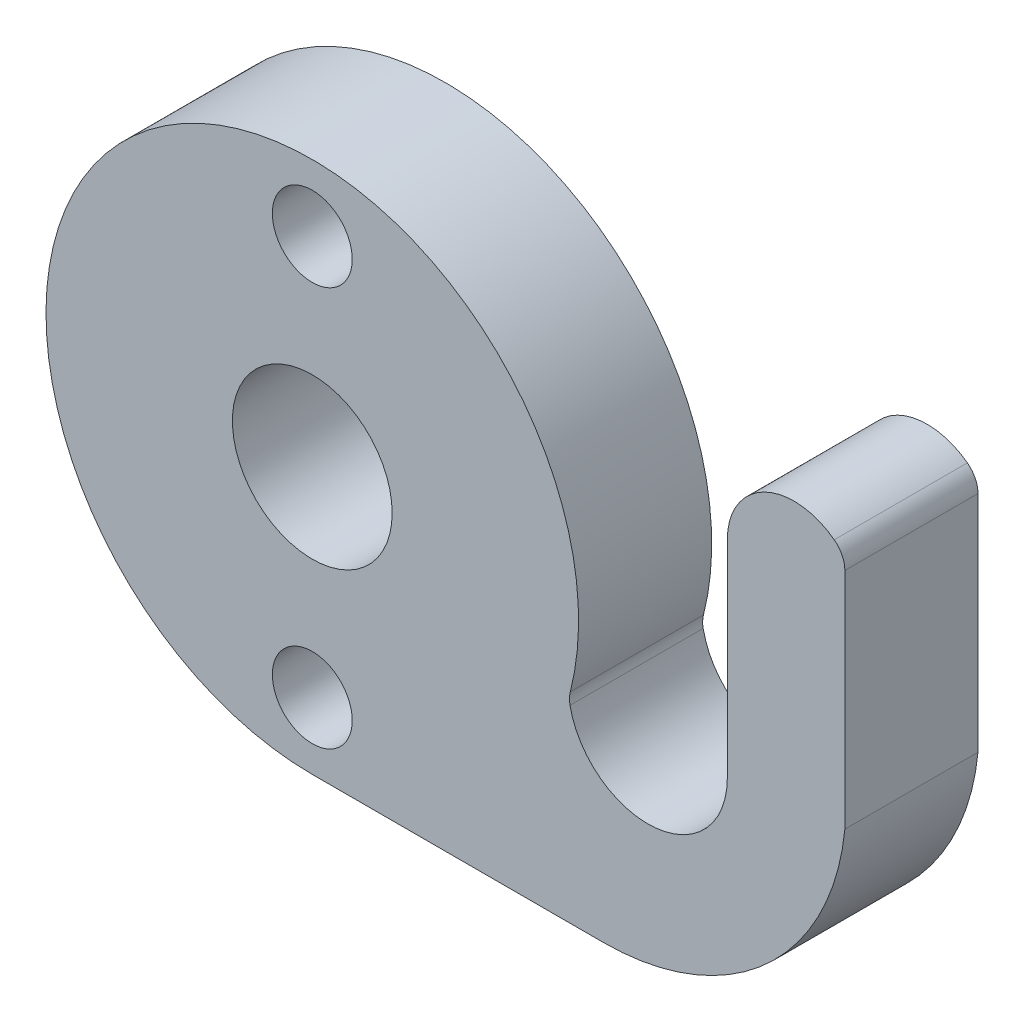
SolidWorks part; units mm, degrees
ref_plane "Front" through (0, 0, 0) normal (0, 0, 1) x (1, 0, 0)
ref_plane "Top" through (0, 0, 0) normal (0, 1, 0) x (1, 0, 0)
ref_plane "Right" through (0, 0, 0) normal (1, 0, 0) x (0, 0, -1)
sketch "Esquisse1" plane through (0, 0, 0) normal (0, 0, 1) x (1, 0, 0)
  line L0 (10.586, -2.3263) -> (10.586, 5.428)
  line L3 (-5, -10) -> (5.9334, -10)
  line L4 (15, 7.0573) -> (15, -1.7796)
  line L5 (-15, 10) -> (0, 0) construction
  line L6 (-15, -10) -> (15, 10) construction
  line L7 (15, 7.0573) -> (15, -1.7796)
  line L8 (-5, -10) -> (5.9334, -10)
  line L9 (7.9353, -5.2902) -> (15, -10) construction
  arc A0 (4.6398, -2.6597) -> (-5, -10) centre (-5, 0) ccw
  arc A1 (4.6398, -2.6597) -> (10.586, -2.3263) centre (7.6035, -2.3263) ccw
  arc A2 (5.9334, -10) -> (15, 0) centre (5.9334, -0.8898) ccw
  arc A3 (10.586, 5.428) -> (15, 7.0573) centre (13.0937, 5.428) cw
  circle A4 centre (-5, 0) radius 3
  circle A5 centre (-5, 7.5) radius 1.5
  circle A6 centre (-5, -7.5) radius 1.5
  point P0 (0, 0)
  point P19 (4.6398, -2.6597)
  point P28 (10.586, 1.5509)
  dimension "D3" = 6
  dimension "D4" = 3
  dimension "D5" = 3
  dimension "D1" = 30
  dimension "D2" = 20
  dimension "D6" = 2.5
  dimension "D7" = 7.5
  dimension "D8" = 5
  dimension "D9" = 7.6035
  dimension "D10" = 10.586
  dimension "D11" = 13.0937
  dimension "D12" = 5.428
  dimension "D13" = 2.3263
  dimension "D14" = 10
  dimension "D15" = 5.9334
  dimension "D16" = 5.9997
  dimension "D17" = 15
extrude "Boss.-Extru.1" add sketch "Esquisse1" along normal blind 5 contours A3 L0 A1 A0 L3 A2 L7 L4 A6 A5 A4
fillet "Congé3" radius 1 1 edges at (15, 7.0573, 2.5)
fillet "Congé7" radius 1 1 edges at (4.6398, -2.6597, 2.5)
